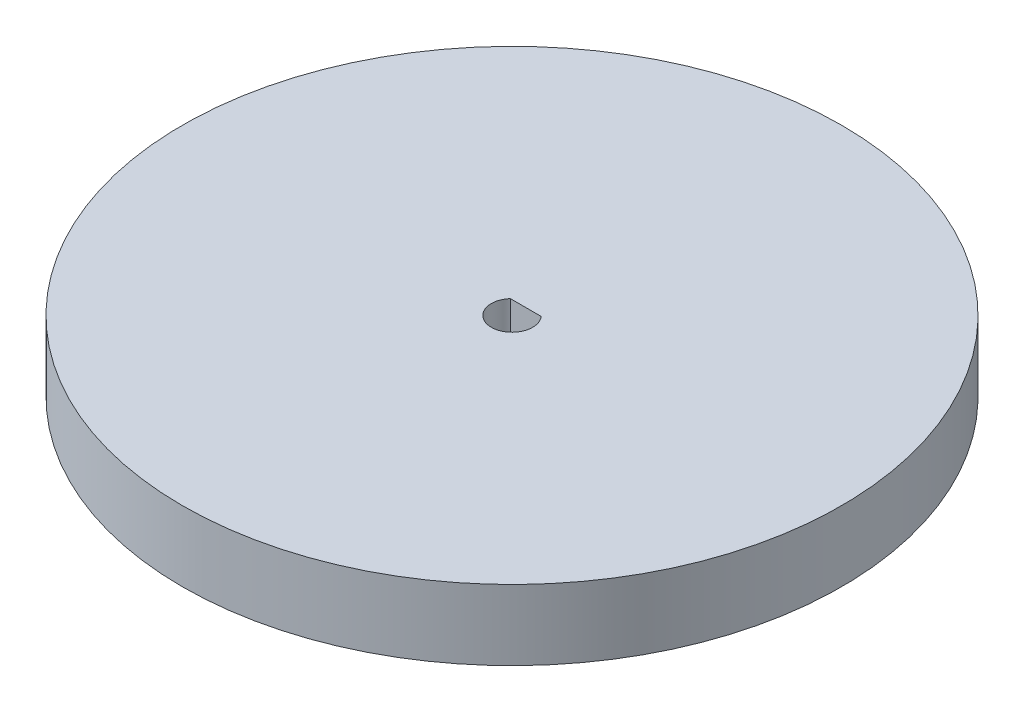
SolidWorks part; units mm, degrees
ref_plane "Front Plane" through (0, 0, 0) normal (0, 0, 1) x (1, 0, 0)
ref_plane "Top Plane" through (0, 0, 0) normal (0, 1, 0) x (1, 0, 0)
ref_plane "Right Plane" through (0, 0, 0) normal (1, 0, 0) x (0, 0, -1)
sketch "Sketch1" plane through (0, 0, 0) normal (0, 1, 0) x (1, 0, 0)
  line L0 (0, 25.5524) -> (0, 22.0218) construction
  circle A0 centre (0, 0) radius 25.5524 construction
  circle A1 centre (0, 0) radius 22.0218 construction
  circle A2 centre (0, 0) radius 23.8156
  circle A3 centre (0, 23.8156) radius 1.7938 construction
  dimension "D1" = 51.1048
  dimension "D2" = 44.0436
extrude "Boss-Extrude1" add sketch "Sketch1" along normal blind 5.08 contours A2
sketch "Sketch2" plane through (0, 5.08, 0) normal (0, 1, 0) x (1, 0, 0)
  line L0 (0, 1.4922) -> (0, -1.4922) construction
  line L1 (-1.1146, 0.9922) -> (1.1146, 0.9922) construction
  line L2 (-1.1146, 0.9922) -> (1.1146, 0.9922)
  arc A0 (-1.1146, 0.9922) -> (1.1146, 0.9922) centre (0, 0) ccw construction
  arc A1 (-1.1146, 0.9922) -> (1.1146, 0.9922) centre (0, 0) ccw
  dimension "D1" = 2.9845
  dimension "D2" = 0.5
extrude "Cut-Extrude1" cut sketch "Sketch2" against normal blind 5.08
